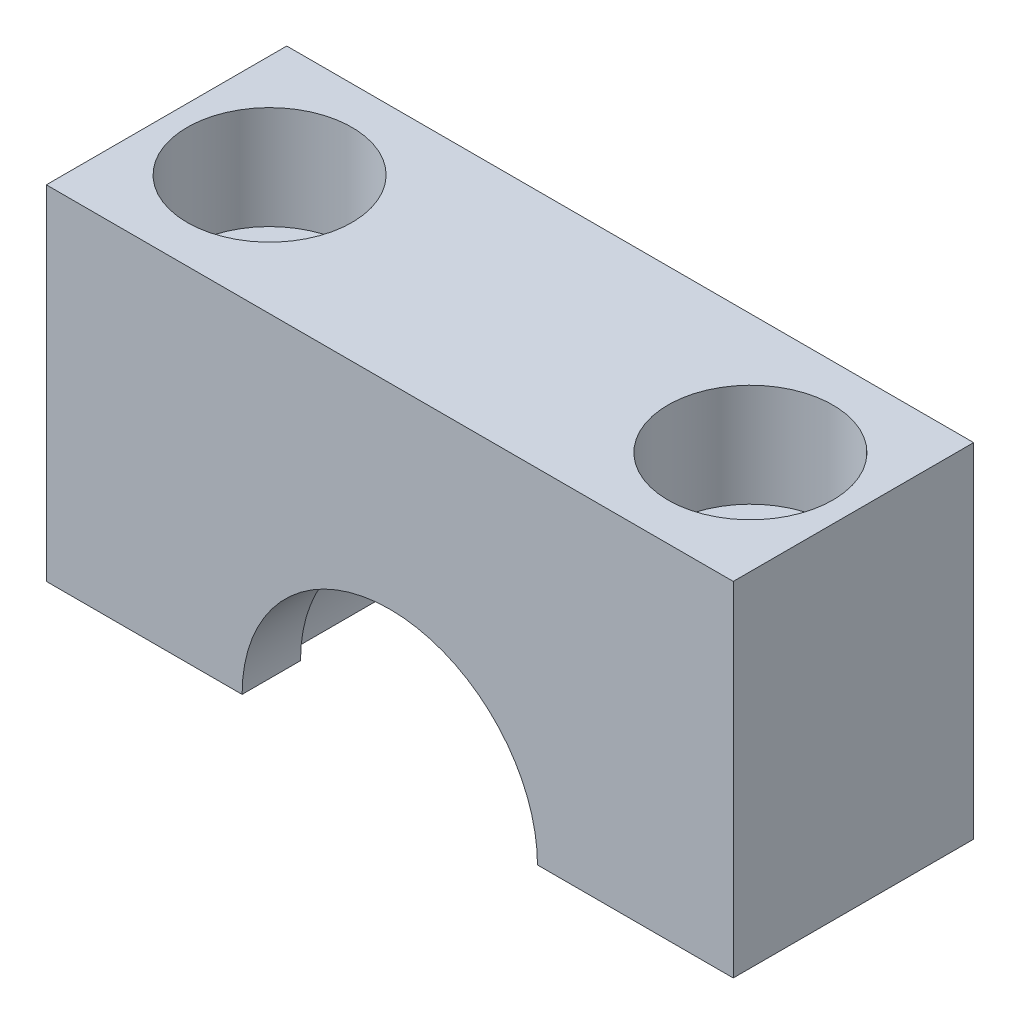
SolidWorks part; units mm, degrees
ref_plane "前视基准面" through (0, 0, 0) normal (0, 0, 1) x (1, 0, 0)
ref_plane "上视基准面" through (0, 0, 0) normal (0, 1, 0) x (1, 0, 0)
ref_plane "右视基准面" through (0, 0, 0) normal (1, 0, 0) x (0, 0, -1)
sketch "草图1" plane through (0, 0, 0) normal (0, 0, 1) x (1, 0, 0)
  line L0 (21.5, -25) -> (50, -25)
  line L1 (-50, 25) -> (50, 25)
  line L2 (-50, 25) -> (-50, -25)
  line L3 (-50, -25) -> (-21.5, -25)
  line L4 (50, 25) -> (50, -25)
  line L5 (-50, 25) -> (50, -25) construction
  line L6 (-50, -25) -> (50, 25) construction
  arc A0 (21.5, -25) -> (-21.5, -25) centre (0, -25) ccw
  point P0 (0, 0)
  dimension "D3" = 43
  dimension "D1" = 100
  dimension "D2" = 50
  dimension "D4" = 28.5
  dimension "D5" = 28.5
extrude "凸台-拉伸1" add sketch "草图1" along normal mid plane 35
sketch "草图2" plane through (0, 25, 0) normal (0, 1, 0) x (1, 0, 0)
  line L0 (-50, 0) -> (50, 0) construction
  line L1 (-50, -17.5) -> (-50, 17.5) construction
  line L2 (50, -17.5) -> (50, 17.5) construction
  line L3 (-35, 17.5) -> (-35, -17.5) construction
  line L4 (50, 17.5) -> (-50, 17.5) construction
  line L5 (50, -17.5) -> (-50, -17.5) construction
  line L6 (35, 17.5) -> (35, -17.5) construction
  circle A0 centre (-35, 0) radius 7.5
  circle A1 centre (35, 0) radius 7.5
  dimension "D3" = 15
  dimension "D4" = 15
  dimension "D1" = 15
  dimension "D2" = 15
extrude "切除-拉伸1" cut sketch "草图2" against normal through all
sketch "草图3" plane through (0, 25, 0) normal (0, 1, 0) x (1, 0, 0)
  circle A0 centre (-35, 0) radius 12
  circle A1 centre (35, 0) radius 12
  dimension "D1" = 24
  dimension "D2" = 24
extrude "切除-拉伸2" cut sketch "草图3" against normal blind 15
sketch "草图4" plane through (0, 0, 0) normal (0, 0, 1) x (1, 0, 0)
  circle A0 centre (0, -25) radius 23.5
  dimension "D1" = 47
extrude "切除-拉伸3" cut sketch "草图4" against normal mid plane 18
